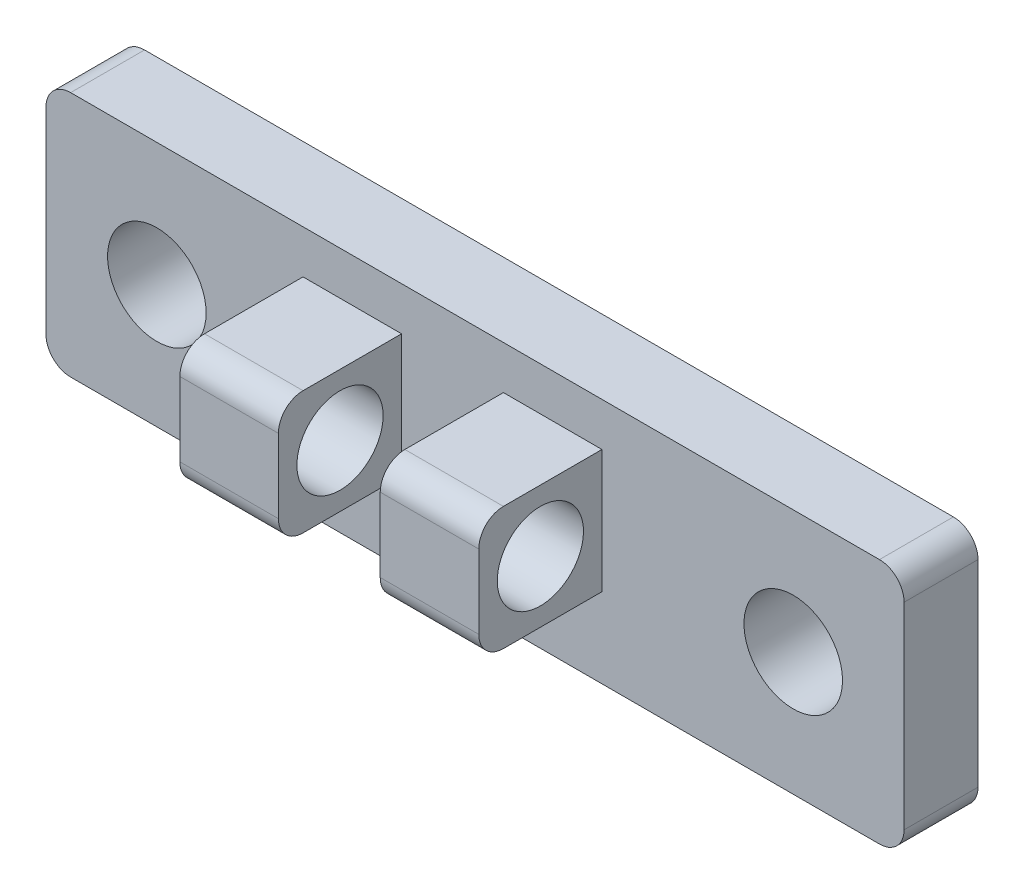
SolidWorks part; units mm, degrees
ref_plane "Front Plane" through (0, 0, 0) normal (0, 0, 1) x (1, 0, 0)
ref_plane "Top Plane" through (0, 0, 0) normal (0, 1, 0) x (1, 0, 0)
ref_plane "Right Plane" through (0, 0, 0) normal (1, 0, 0) x (0, 0, -1)
sketch "Sketch1" plane through (0, 0, 0) normal (0, 0, 1) x (1, 0, 0)
  line L0 (17.8423, -3.3213) -> (17.8423, -10.7913)
  line L5 (16.1623, -1.6413) -> (-16.1377, -1.6413)
  line L7 (-16.9877, -2.4913) -> (-16.9877, -9.5055)
  line L8 (-16.9877, -2.4913) -> (-16.9877, -1.6413)
  line L9 (-16.9877, -1.6413) -> (-16.1377, -1.6413)
  line L10 (17.8423, -3.3213) -> (17.8423, -1.6413)
  line L11 (17.8423, -1.6413) -> (16.1623, -1.6413)
  line L12 (16.9923, -11.6413) -> (17.8423, -11.6413)
  line L13 (17.8423, -11.6413) -> (17.8423, -10.7913)
  line L14 (-16.9877, -9.5055) -> (-16.9877, -11.6413)
  line L15 (-16.9877, -11.6413) -> (-15.3077, -11.6413)
  line L25 (16.9923, -11.6413) -> (-15.3077, -11.6413)
  dimension "D1" = 34.83
  dimension "D2" = 10
extrude "Boss-Extrude1" add sketch "Sketch1" along normal blind 3 contours L25 L15 L14 L7 L8 L9 L5 L11 L10 L0 L13 L12
sketch "Sketch2" plane through (0, 0, 3) normal (0, 0, 1) x (1, 0, 0)
  line L3 (-2.5546, -8.4024) -> (-6.5546, -8.4024)
  line L4 (-2.5546, -8.4024) -> (-2.5546, -3.4024)
  line L5 (-2.5546, -3.4024) -> (-6.5546, -3.4024)
  line L6 (-6.5546, -8.4024) -> (-6.5546, -3.4024)
  line L9 (5.5788, -3.4024) -> (1.5788, -3.4024)
  line L10 (1.5788, -8.4024) -> (1.5788, -3.4024)
  line L11 (5.5788, -8.4024) -> (1.5788, -8.4024)
  line L12 (5.5788, -8.4024) -> (5.5788, -3.4024)
  point P5 (-2.5546, -8.4024)
  point P6 (-6.5546, -3.4024)
  point P7 (0, 0)
  dimension "D1" = 4
  dimension "D2" = 4
extrude "Boss-Extrude2" add sketch "Sketch2" along normal blind 5
sketch "Sketch3" plane through (5.5788, 0, 0) normal (1, 0, 0) x (0, 0, -1)
  line L0 (-8, -8.4024) -> (-8, -3.4024) construction
  circle A0 centre (-5.5, -5.9024) radius 1.75
  dimension "D1" = 2.5
extrude "Cut-Extrude1" cut sketch "Sketch3" against normal blind 14
fillet "Fillet1" radius 1 4 edges at (17.8423, -11.6413, 1.5) (17.8423, -1.6413, 1.5) (-16.9877, -1.6413, 1.5) (-16.9877, -11.6413, 1.5)
sketch "Sketch5" plane through (0, 0, 3) normal (0, 0, 1) x (1, 0, 0)
  line L0 (-16.9877, -10.6413) -> (-16.9877, -2.6413) construction
  circle A0 centre (-12.4877, -6.6413) radius 2
  dimension "D1" = 4.5
extrude "Cut-Extrude2" cut sketch "Sketch5" against normal blind 5
sketch "Sketch7" plane through (0, 0, 3) normal (0, 0, 1) x (1, 0, 0)
  line L0 (17.8423, -10.6413) -> (17.8423, -2.6413) construction
  line L1 (-15.9877, -11.6413) -> (16.8423, -11.6413) construction
  circle A0 centre (13.3423, -6.6413) radius 2
  dimension "D1" = 4.5
  dimension "D2" = 5
extrude "Cut-Extrude3" cut sketch "Sketch7" against normal blind 5
fillet "Fillet2" radius 1 4 edges at (-4.5546, -8.4024, 8) (-4.5546, -3.4024, 8) (3.5788, -8.4024, 8) (3.5788, -3.4024, 8)
